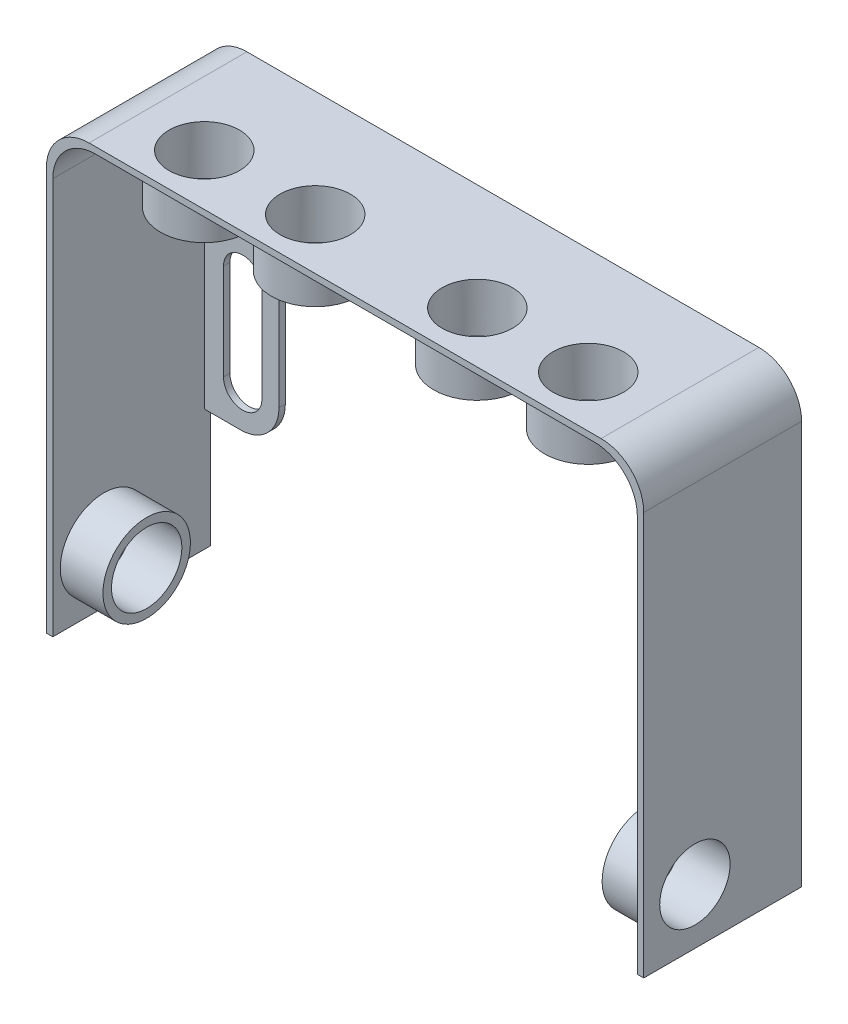
SolidWorks part; units mm, degrees
ref_plane "Ebene vorne" through (0, 0, 0) normal (0, 0, 1) x (1, 0, 0)
ref_plane "Ebene oben" through (0, 0, 0) normal (0, 1, 0) x (1, 0, 0)
ref_plane "Ebene rechts" through (0, 0, 0) normal (1, 0, 0) x (0, 0, -1)
sketch "Skizze1" plane through (0, 0, 0) normal (0, 0, 1) x (1, 0, 0)
  line L1 (0, 0) -> (140, 0)
  line L2 (0, 0) -> (0, 209.01)
  line L3 (0, 209.01) -> (140, 209.01)
  line L4 (140, 0) -> (140, 209.01)
  line L5 (1.5, 207.51) -> (138.5, 207.51)
  line L6 (1.5, 207.51) -> (1.5, 1.5)
  line L7 (1.5, 1.5) -> (138.5, 1.5)
  line L8 (138.5, 207.51) -> (138.5, 1.5)
  dimension "D1" = 140
  dimension "D2" = 209.01
  dimension "D3" = 1.5
  dimension "D4" = 1.5
  dimension "D5" = 1.5
  dimension "D6" = 1.5
extrude "Aufsatz-Linear austragen1" add sketch "Skizze1" along normal blind 37
fillet "Verrundung1" radius 10 8 edges at (140, 0, 18.5) (1.5, 207.51, 18.5) (140, 209.01, 18.5) (0, 209.01, 18.5) (0, 0, 18.5) (1.5, 1.5, 18.5) (138.5, 1.5, 18.5) (138.5, 207.51, 18.5)
sketch "Skizze3" plane through (0, 209.01, 0) normal (0, 1, 0) x (1, 0, 0)
  line L0 (130, 0) -> (10, 0) construction
  line L1 (0, -37) -> (0, 0) construction
  line L6 (70, 0) -> (70, -37) construction
  line L7 (130, -37) -> (10, -37) construction
  circle A0 centre (25, -25) radius 8.25
  circle A1 centre (51, -25) radius 8.25
  circle A2 centre (89, -25) radius 8.25
  circle A3 centre (115, -25) radius 8.25
  dimension "D1" = 16.5
  dimension "D2" = 26
  dimension "D3" = 25
  dimension "D4" = 25
extrude "Schnitt-Linear austragen1" cut sketch "Skizze3" against normal up to surface (1.5 mm away) up to face at (70, 207.51, 18.5)
sketch "Skizze4" plane through (140, 0, 0) normal (1, 0, 0) x (0, 0, -1)
  line L0 (-37, 104.505) -> (0, 104.505) construction
  line L1 (-37, 10) -> (-37, 199.01) construction
  line L2 (0, 10) -> (0, 199.01) construction
  circle A0 centre (-25, 117.505) radius 8.25
  circle A1 centre (-25, 91.505) radius 8.25
  dimension "D2" = 16.5
  dimension "D1" = 26
  dimension "D3" = 25
extrude "Schnitt-Linear austragen2" cut sketch "Skizze4" against normal through all both and the other way through all
sketch "Skizze5" plane through (0, 0, 0) normal (0, 0, -1) x (-1, 0, 0)
  line L0 (0, 153.01) -> (-19, 153.01) construction
  line L5 (-130, 209.01) -> (-10, 209.01) construction
  line L10 (0, 199.01) -> (0, 10) construction
  line L13 (-70, 209.01) -> (-70, 0) construction
  line L16 (-10, 0) -> (-130, 0) construction
  line L17 (-32.7994, 104.505) -> (-114.9075, 104.505) construction
  line L19 (-140, 153.01) -> (-121, 153.01) construction
  line L20 (-140, 173.01) -> (-130, 173.01)
  line L23 (-140, 173.01) -> (-140, 133.01)
  line L34 (-58.75, 195.51) -> (-81.25, 195.51) construction
  line L35 (-58.75, 200.01) -> (-81.25, 200.01)
  line L36 (-58.75, 191.01) -> (-81.25, 191.01)
  line L37 (-10.5, 164.26) -> (-10.5, 141.76) construction
  line L38 (-15, 164.26) -> (-15, 141.76)
  line L39 (-6, 164.26) -> (-6, 141.76)
  line L40 (-140, 133.01) -> (-130, 133.01)
  line L43 (-121, 164.01) -> (-121, 142.01)
  line L54 (-90, 209.01) -> (-90, 196.01)
  line L55 (-59, 187.01) -> (-81, 187.01)
  line L56 (-50, 209.01) -> (-50, 196.01)
  line L57 (-50, 209.01) -> (-90, 209.01)
  line L58 (-19, 164.01) -> (-19, 142.01)
  line L59 (0, 133.01) -> (-10, 133.01)
  line L60 (0, 173.01) -> (0, 133.01)
  line L61 (0, 173.01) -> (-10, 173.01)
  line L62 (-70, 209.01) -> (-70, 187.01) construction
  line L67 (-129.5, 164.26) -> (-129.5, 141.76) construction
  line L68 (-125, 164.26) -> (-125, 141.76)
  line L69 (-134, 164.26) -> (-134, 141.76)
  line L73 (-10.5, 44.75) -> (-10.5, 67.25) construction
  line L74 (-15, 44.75) -> (-15, 67.25)
  line L75 (-6, 44.75) -> (-6, 67.25)
  line L76 (-129.5, 44.75) -> (-129.5, 67.25) construction
  line L77 (-125, 44.75) -> (-125, 67.25)
  line L78 (-134, 44.75) -> (-134, 67.25)
  line L79 (-140, 56) -> (-121, 56) construction
  line L80 (0, 56) -> (-19, 56) construction
  line L81 (0, 36) -> (-10, 36)
  line L82 (0, 36) -> (0, 76)
  line L83 (0, 76) -> (-10, 76)
  line L84 (-19, 45) -> (-19, 67)
  line L85 (-121, 45) -> (-121, 67)
  line L86 (-140, 76) -> (-130, 76)
  line L87 (-140, 36) -> (-140, 76)
  line L88 (-140, 36) -> (-130, 36)
  arc A8 (-58.75, 200.01) -> (-58.75, 191.01) centre (-58.75, 195.51) cw
  arc A9 (-81.25, 191.01) -> (-81.25, 200.01) centre (-81.25, 195.51) cw
  arc A10 (-15, 164.26) -> (-6, 164.26) centre (-10.5, 164.26) cw
  arc A11 (-6, 141.76) -> (-15, 141.76) centre (-10.5, 141.76) cw
  arc A16 (-90, 196.01) -> (-81, 187.01) centre (-81, 196.01) ccw
  arc A17 (-59, 187.01) -> (-50, 196.01) centre (-59, 196.01) ccw
  arc A18 (-19, 142.01) -> (-10, 133.01) centre (-10, 142.01) ccw
  arc A19 (-19, 164.01) -> (-10, 173.01) centre (-10, 164.01) cw
  arc A20 (-121, 164.01) -> (-130, 173.01) centre (-130, 164.01) ccw
  arc A21 (-121, 142.01) -> (-130, 133.01) centre (-130, 142.01) cw
  arc A24 (-125, 164.26) -> (-134, 164.26) centre (-129.5, 164.26) ccw
  arc A25 (-134, 141.76) -> (-125, 141.76) centre (-129.5, 141.76) ccw
  arc A28 (-15, 44.75) -> (-6, 44.75) centre (-10.5, 44.75) ccw
  arc A29 (-6, 67.25) -> (-15, 67.25) centre (-10.5, 67.25) ccw
  arc A30 (-125, 44.75) -> (-134, 44.75) centre (-129.5, 44.75) cw
  arc A31 (-134, 67.25) -> (-125, 67.25) centre (-129.5, 67.25) cw
  arc A32 (-121, 67) -> (-130, 76) centre (-130, 67) ccw
  arc A33 (-121, 45) -> (-130, 36) centre (-130, 45) cw
  arc A34 (-19, 45) -> (-10, 36) centre (-10, 45) ccw
  arc A35 (-19, 67) -> (-10, 76) centre (-10, 67) cw
  point P42 (-129.5, 153.01)
  point P58 (-70, 195.51)
  point P65 (-10.5, 153.01)
  point P70 (-10.5, 56)
  point P77 (-129.5, 56)
  point P105 (-90, 187.01)
  point P108 (-50, 187.01)
  dimension "D4" = 9
  dimension "D10" = 9
  dimension "D1" = 9
  dimension "D2" = 22.5
  dimension "D3" = 40
  dimension "D6" = 13.5
  dimension "D7" = 9
  dimension "D8" = 22.5
  dimension "D9" = 4
  dimension "D11" = 40
  dimension "D12" = 10.5
  dimension "D13" = 4
  dimension "D14" = 56
  dimension "D15" = 104.505
extrude "Aufsatz-Linear austragen3" add sketch "Skizze5" against normal blind 1.5
sketch "Skizze6" plane through (0, 0, 1.5) normal (0, 0, 1) x (1, 0, 0)
  line L0 (130, 209.01) -> (10, 209.01) construction
  line L1 (-30.9644, 104.505) -> (199.5516, 104.505)
  line L2 (-30.9644, 104.505) -> (-30.9644, -15.0602)
  line L3 (-30.9644, -15.0602) -> (199.5516, -15.0602)
  line L4 (199.5516, 104.505) -> (199.5516, -15.0602)
  dimension "D1" = 104.505
extrude "Schnitt-Linear austragen3" cut sketch "Skizze6" against normal through all both and the other way through all
sketch "Skizze7" plane through (0, 207.51, 0) normal (0, -1, 0) x (1, 0, 0)
  line L0 (70, 37) -> (70, -3.7459) construction
  line L1 (128.5, 37) -> (11.5, 37) construction
  circle A0 centre (51, 25) radius 10.25
  circle A1 centre (25, 25) radius 10.25
  circle A2 centre (25, 25) radius 8.25 construction
  circle A3 centre (115, 25) radius 10.25
  circle A4 centre (89, 25) radius 10.25
  circle A5 centre (25, 25) radius 8.25
  circle A6 centre (51, 25) radius 8.25
  circle A7 centre (89, 25) radius 8.25
  circle A8 centre (115, 25) radius 8.25
  dimension "D1" = 2
extrude "Aufsatz-Linear austragen4" add sketch "Skizze7" along normal blind 10
sketch "Skizze8" plane through (1.5, 0, 0) normal (1, 0, 0) x (0, 0, -1)
  circle A0 centre (-25, 117.505) radius 8.25
  circle A1 centre (-25, 117.505) radius 10.25
  circle A2 centre (-25, 117.505) radius 8.25 construction
  dimension "D1" = 2
extrude "Aufsatz-Linear austragen5" add sketch "Skizze8" along normal blind 10
ref_plane "Ebene1" through (70, 0, 0) normal (-1, 0, 0) x (0, 0, 1)
mirror "Spiegeln1" about plane through (70, 0, 0) normal (-1, 0, 0) of "Aufsatz-Linear austragen5"
